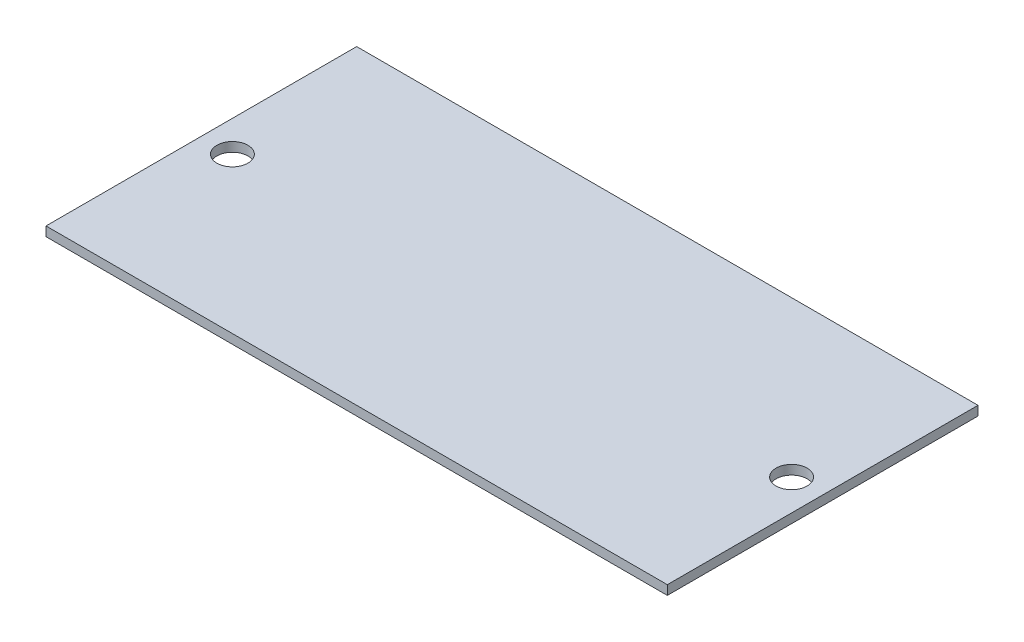
SolidWorks part; units mm, degrees
ref_plane "Plano frontal" through (0, 0, 0) normal (0, 0, 1) x (1, 0, 0)
ref_plane "Plano superior" through (0, 0, 0) normal (0, 1, 0) x (1, 0, 0)
ref_plane "Plano direito" through (0, 0, 0) normal (1, 0, 0) x (0, 0, -1)
sketch "Esboço5" plane through (0, 0, 0) normal (0, 1, 0) x (1, 0, 0)
  line L1 (-52.0366, 35.9137) -> (47.9634, 35.9137)
  line L2 (-52.0366, 35.9137) -> (-52.0366, -14.0863)
  line L3 (-52.0366, -14.0863) -> (47.9634, -14.0863)
  line L4 (47.9634, 35.9137) -> (47.9634, -14.0863)
  circle A0 centre (-47.052, 10.8751) radius 2.5
  circle A1 centre (42.9792, 10.8751) radius 2.5
  point P8 (37.4531, 11.1033)
  point P9 (0, 0)
  point P10 (-40.3646, 11.4794)
  point P11 (-42.3473, 11.6033)
  point P12 (-45.1975, 11.7272)
  point P13 (0, 0)
  point P14 (-45.2505, 11.1033)
  point P15 (0, 0)
  point P16 (0, 0)
  point P17 (-45.9453, 11.1033)
  point P18 (0, 0)
  point P19 (0, 0)
  point P20 (-46.4791, 11.1033)
  point P21 (-46.8461, 11.1033)
  point P22 (-46.9128, 10.8594)
  point P23 (-46.9759, 10.8989)
  point P24 (-47.05, 11.1033)
  point P25 (0, 0)
  point P26 (0, 0)
  point P27 (43.9013, 11.1033)
  point P28 (44.1332, 11.1033)
  point P29 (43.7748, 11.1033)
  point P30 (43.9856, 11.1033)
  point P31 (43.9833, 11.1033)
  point P32 (-46.5445, 11.1033)
  point P33 (43.0128, 11.1033)
  point P34 (43.3994, 11.1033)
  point P35 (43.641, 11.1033)
  point P36 (43.4718, 11.1033)
  point P37 (-46.9766, 11.1033)
  point P38 (-47.1026, 11.1033)
  point P39 (-46.9514, 11.1033)
  point P40 (-47.0396, 11.1033)
  point P41 (42.9918, 11.1033)
  point P42 (-47.0572, 10.7634)
  point P43 (0, 0)
  point P44 (-47.0388, 10.9699)
  point P45 (-47.0641, 10.8143)
  point P46 (-47.052, 10.8751)
  point P47 (42.9792, 10.8751)
extrude "Ressalto-extrusão1" add sketch "Esboço5" along normal blind 1.5 contours L1 L4 L3 L2
sketch "Esboço6" plane through (0, 0, 0) normal (0, -1, 0) x (-1, 0, 0)
  line L1 (52.0366, 35.9137) -> (52.0366, -14.0863) construction
  line L2 (52.0366, -14.0863) -> (-47.9634, -14.0863) construction
  line L3 (-47.9634, 35.9137) -> (-47.9634, -14.0863) construction
  circle A0 centre (47.0366, 10.9137) radius 2.5
  circle A1 centre (-42.9634, 10.9137) radius 2.5
  dimension "D1" = 5
  dimension "D2" = 25
  dimension "D3" = 5
  dimension "D4" = 25
extrude "Corte-extrusão1" cut sketch "Esboço6" against normal through all
